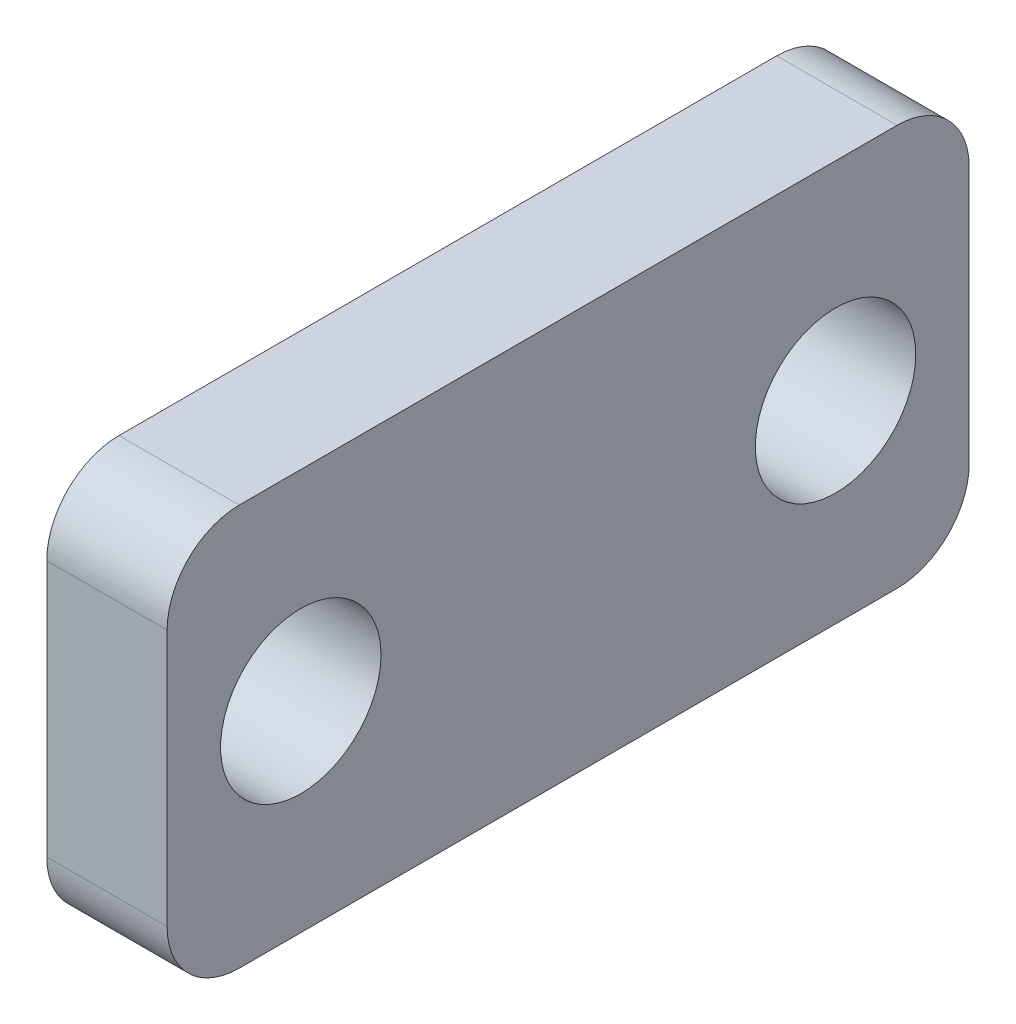
SolidWorks part; units mm, degrees
ref_plane "Ön Düzlem" through (0, 0, 0) normal (0, 0, 1) x (1, 0, 0)
ref_plane "Üst Düzlem" through (0, 0, 0) normal (0, 1, 0) x (1, 0, 0)
ref_plane "Sağ Düzlem" through (0, 0, 0) normal (1, 0, 0) x (0, 0, -1)
sketch "Çizim1" plane through (0, 0, 0) normal (1, 0, 0) x (0, 0, -1)
  line L1 (-123, 75) -> (123, 75)
  line L2 (-150, 48) -> (-150, -48)
  line L3 (-123, -75) -> (123, -75)
  line L4 (150, 48) -> (150, -48)
  line L5 (-150, 75) -> (150, -75) construction
  line L6 (-150, -75) -> (150, 75) construction
  arc A0 (-123, -75) -> (-150, -48) centre (-123, -48) cw
  arc A1 (123, -75) -> (150, -48) centre (123, -48) ccw
  arc A2 (150, 48) -> (123, 75) centre (123, 48) ccw
  arc A3 (-150, 48) -> (-123, 75) centre (-123, 48) cw
  point P0 (0, 0)
  dimension "D3" = 27
  dimension "D1" = 300
  dimension "D2" = 150
extrude "Yükseklik-Ekstrüzyon1" add sketch "Çizim1" along normal blind 45
sketch "Çizim2" plane through (45, 0, 0) normal (1, 0, 0) x (0, 0, -1)
  circle A0 centre (100, -2.6342) radius 30
  circle A1 centre (-100, 0) radius 30
extrude "Kes-Ekstrüzyon2" cut sketch "Çizim2" against normal blind 45
